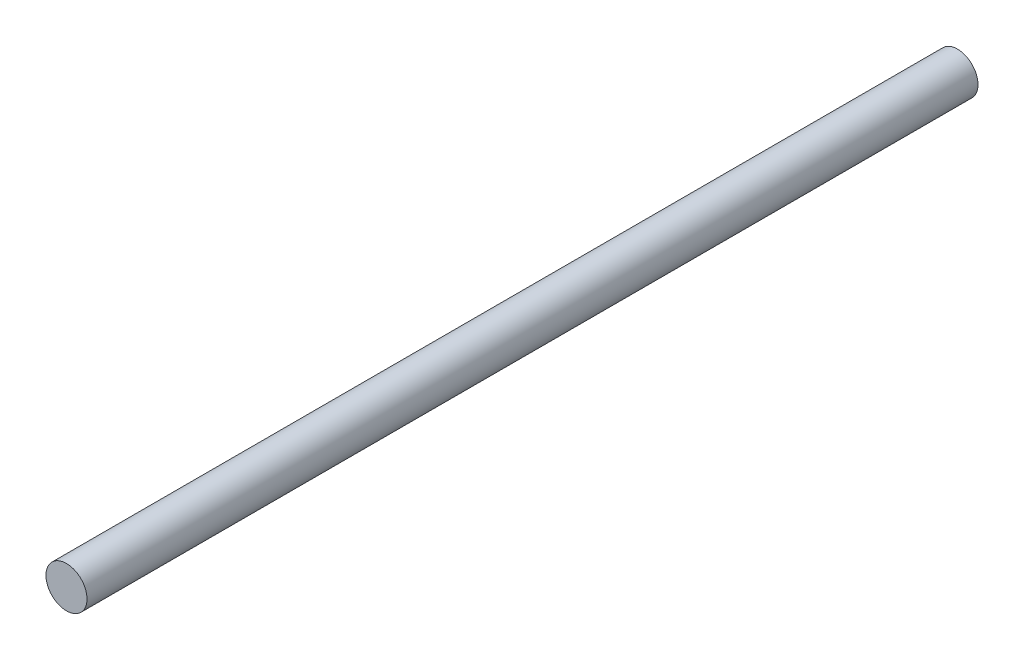
SolidWorks part; units mm, degrees
material "AISI 1020 Steel, Cold Rolled"
ref_plane "Płaszczyzna przednia" through (0, 0, 0) normal (0, 0, 1) x (1, 0, 0)
ref_plane "Płaszczyzna górna" through (0, 0, 0) normal (0, 1, 0) x (1, 0, 0)
ref_plane "Płaszczyzna prawa" through (0, 0, 0) normal (1, 0, 0) x (0, 0, -1)
sketch "Szkic1" plane through (0, 0, 0) normal (0, 0, 1) x (1, 0, 0)
  circle A0 centre (0, 0) radius 5
  dimension "D1" = 10
extrude "Dodanie-wyciągnięcie1" add sketch "Szkic1" along normal blind 217
